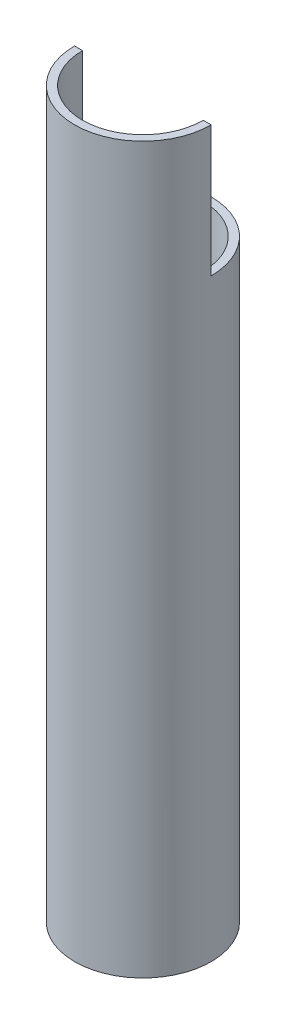
SolidWorks part; units mm, degrees
material "Thornel Mat VMA"
ref_plane "Front Plane" through (0, 0, 0) normal (0, 0, 1) x (1, 0, 0)
ref_plane "Top Plane" through (0, 0, 0) normal (0, 1, 0) x (1, 0, 0)
ref_plane "Right Plane" through (0, 0, 0) normal (1, 0, 0) x (0, 0, -1)
sketch "Sketch1" plane through (0, 0, 0) normal (0, 1, 0) x (1, 0, 0)
  circle A0 centre (0, 0) radius 14.375
  circle A1 centre (0, 0) radius 12.7
  dimension "D1" = 25.4
  dimension "D2" = 28.75
extrude "Boss-Extrude1" add sketch "Sketch1" along normal blind 152.5
sketch "Sketch2" plane through (0, 152.5, 0) normal (0, 1, 0) x (1, 0, 0)
  line L1 (-14.375, 0) -> (15.3413, 0)
  line L2 (-14.375, 0) -> (-14.375, 15.5555)
  line L3 (-14.375, 15.5555) -> (15.3413, 15.5555)
  line L4 (15.3413, 0) -> (15.3413, 15.5555)
  circle A0 centre (0, 0) radius 14.375 construction
extrude "Cut-Extrude1" cut sketch "Sketch2" against normal blind 27.5
